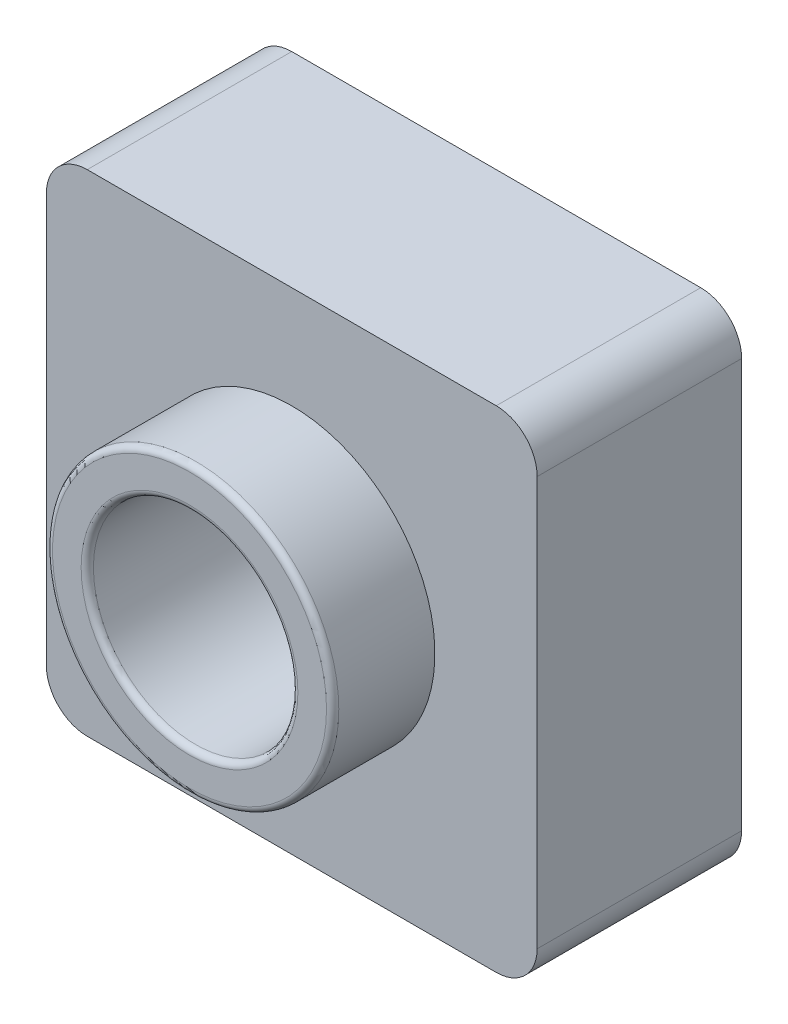
SolidWorks part; units mm, degrees
ref_plane "Front Plane" through (0, 0, 0) normal (0, 0, 1) x (1, 0, 0)
ref_plane "Top Plane" through (0, 0, 0) normal (0, 1, 0) x (1, 0, 0)
ref_plane "Right Plane" through (0, 0, 0) normal (1, 0, 0) x (0, 0, -1)
sketch "Sketch1" plane through (0, 0, 0) normal (0, 0, 1) x (1, 0, 0)
  line L1 (0, 0) -> (120, 0)
  line L2 (0, 0) -> (0, 120)
  line L3 (0, 120) -> (120, 120)
  line L4 (120, 0) -> (120, 120)
  dimension "D1" = 120
  dimension "D2" = 120
extrude "Boss-Extrude1" add sketch "Sketch1" along normal blind 50
sketch "Sketch2" plane through (0, 0, 50) normal (0, 0, 1) x (1, 0, 0)
  line L0 (120, 120) -> (0, 120) construction
  line L1 (120, 0) -> (120, 120) construction
  circle A0 centre (60, 60) radius 35
  dimension "D1" = 70
  dimension "D2" = 60
  dimension "D3" = 60
extrude "Boss-Extrude2" add sketch "Sketch2" along normal blind 25
sketch "Sketch3" plane through (0, 0, 75) normal (0, 0, 1) x (1, 0, 0)
  circle A0 centre (60, 60) radius 25
  dimension "D1" = 50
extrude "Cut-Extrude1" cut sketch "Sketch3" against normal through all
fillet "Fillet1" radius 10 4 edges at (0, 0, 25) (120, 0, 25) (120, 120, 25) (0, 120, 25)
fillet "Fillet2" radius 1.5 2 edges at (95, 60, 75) (85, 60, 75)
shell "Shell1" thickness 2
